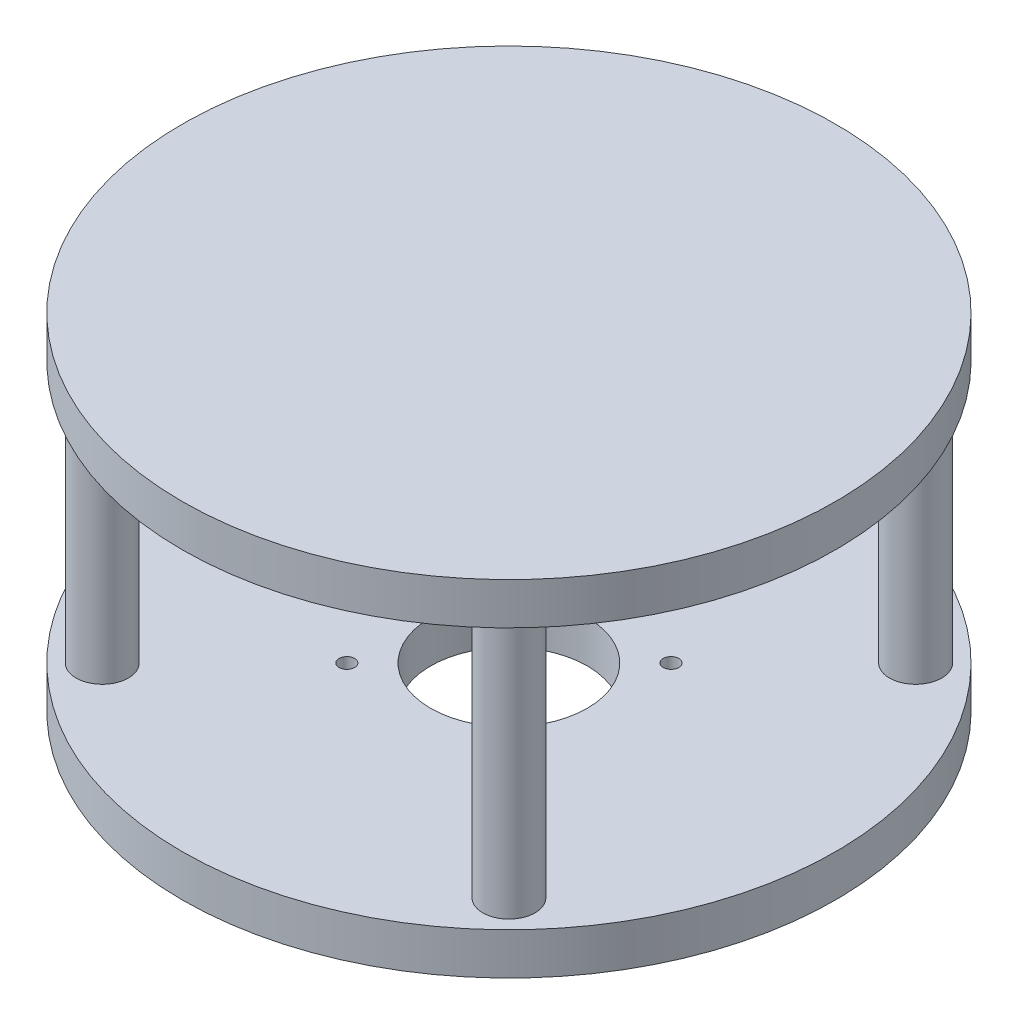
SolidWorks part; units mm, degrees
ref_plane "前视基准面" through (0, 0, 0) normal (0, 0, 1) x (1, 0, 0)
ref_plane "上视基准面" through (0, 0, 0) normal (0, 1, 0) x (1, 0, 0)
ref_plane "右视基准面" through (0, 0, 0) normal (1, 0, 0) x (0, 0, -1)
sketch "草图2" plane through (0, 0, 0) normal (0, 1, 0) x (1, 0, 0)
  circle A0 centre (0, 0) radius 62.5
  dimension "D1" = 125
extrude "凸台-拉伸1" add sketch "草图2" along normal blind 8 contours A0
sketch "草图3" plane through (0, 8, 0) normal (0, 1, 0) x (1, 0, 0)
  line L0 (-62.5, 0) -> (62.5, 0) construction
  line L1 (0, -62.5) -> (0, 62.5) construction
  line L2 (38.8909, 38.8909) -> (0, 0) construction
  circle A0 centre (38.8909, 38.8909) radius 5
  circle A1 centre (0, 0) radius 62.5 construction
  circle A2 centre (38.8909, -38.8909) radius 5
  circle A3 centre (-38.8909, -38.8909) radius 5
  circle A4 centre (-38.8909, 38.8909) radius 5
  point P18 (0, 0)
  dimension "D2" = 10
  dimension "D3" = 55
  dimension "D4" = 45
  dimension "D1" = 4
extrude "凸台-拉伸2" add sketch "草图3" along normal blind 50
sketch "草图4" plane through (0, 58, 0) normal (0, 1, 0) x (1, 0, 0)
  circle A0 centre (0, 0) radius 62.5
  circle A1 centre (0, 0) radius 62.5 construction
extrude "凸台-拉伸3" add sketch "草图4" along normal blind 8 contours A0
sketch "草图5" plane through (0, 0, 0) normal (0, -1, 0) x (1, 0, 0)
  circle A0 centre (0, 0) radius 15
  dimension "D1" = 30
extrude "切除-拉伸1" cut sketch "草图5" against normal up to next contours A0
sketch "草图6" plane through (0, 0, 0) normal (0, -1, 0) x (-1, 0, 0)
  line L0 (62.5, 0) -> (-62.5, 0) construction
  line L1 (0, -62.5) -> (0, 62.5) construction
  circle A0 centre (0, 0) radius 62.5 construction
  circle A1 centre (15.5, -15.5) radius 1.5
  circle A2 centre (15.5, 15.5) radius 1.5
  circle A3 centre (-15.5, -15.5) radius 1.5
  circle A4 centre (-15.5, 15.5) radius 1.5
  point P13 (0, 0)
  dimension "D1" = 3
  dimension "D2" = 31
  dimension "D3" = 31
extrude "切除-拉伸2" cut sketch "草图6" against normal up to next
